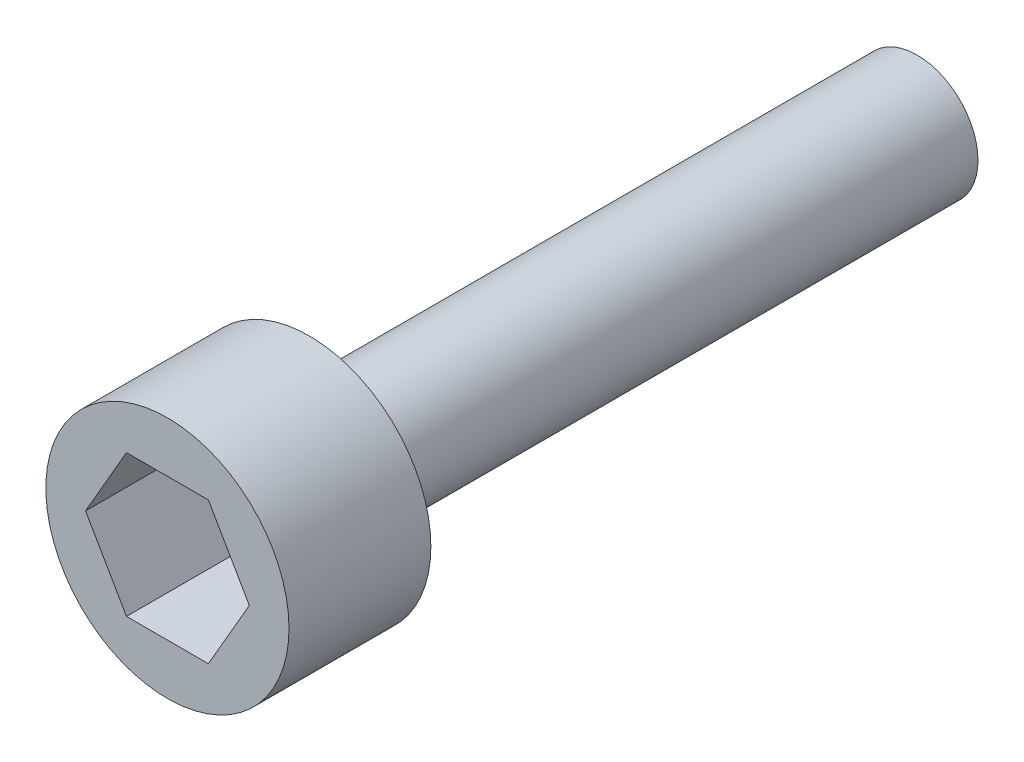
SolidWorks part; units mm, degrees
material "Alloy Steel"
ref_plane "Front Plane" through (0, 0, 0) normal (0, 0, 1) x (1, 0, 0)
ref_plane "Top Plane" through (0, 0, 0) normal (0, 1, 0) x (1, 0, 0)
ref_plane "Right Plane" through (0, 0, 0) normal (1, 0, 0) x (0, 0, -1)
sketch "Sketch1" plane through (0, 0, 0) normal (0, 0, 1) x (1, 0, 0)
  circle A0 centre (0, 0) radius 3
  dimension "D1" = 6
extrude "Head Boss-Extrude1" add sketch "Sketch1" along normal blind 3.5
sketch "Sketch3" plane through (0, 0, 3.5) normal (0, 0, 1) x (1, 0, 0)
  line L0 (-1.0104, 1.75) -> (1.0104, 1.75)
  line L1 (1.0104, 1.75) -> (2.0207, 0)
  line L2 (2.0207, 0) -> (1.0104, -1.75)
  line L3 (1.0104, -1.75) -> (-1.0104, -1.75)
  line L4 (-1.0104, -1.75) -> (-2.0207, 0)
  line L5 (-2.0207, 0) -> (-1.0104, 1.75)
  line L6 (-2.0207, 0) -> (0, 0) construction
  line L7 (2.0207, 0) -> (0, 0) construction
  line L8 (-1.0104, -1.75) -> (0, 0) construction
  line L9 (0, 0) -> (1.0104, 1.75) construction
  line L10 (-1.0104, 1.75) -> (0, 0) construction
  line L11 (0, 0) -> (1.0104, -1.75) construction
  dimension "D1" = 60
  dimension "D2" = 60
  dimension "D3" = 60
  dimension "D4" = 60
  dimension "D5" = 60
  dimension "D6" = 3.5
extrude "Head Hex Cut-Extrude1" cut sketch "Sketch3" against normal blind 2.8
sketch "Sketch2" plane through (0, 0, 0) normal (0, 0, 1) x (1, 0, 0)
  circle A0 centre (0, 0) radius 1.5
  dimension "D1" = 3
extrude "Screw Boss-Extrude2" add sketch "Sketch2" against normal blind 15
